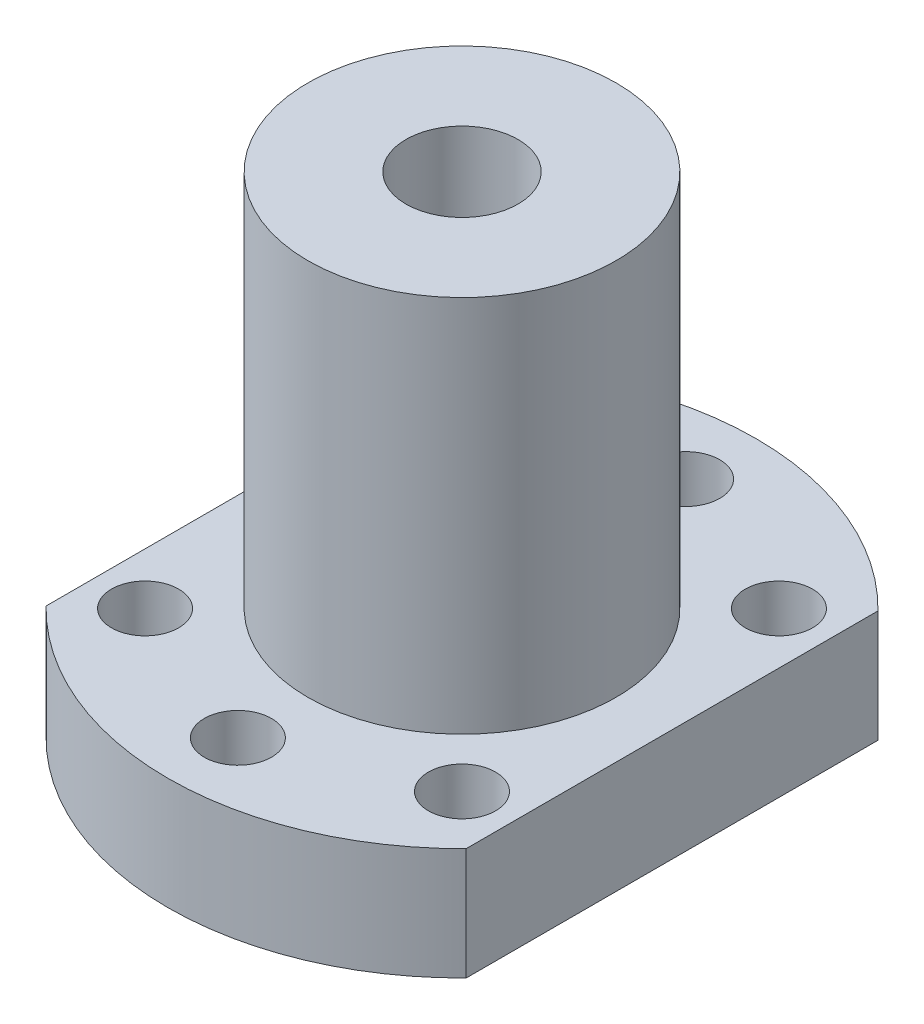
SolidWorks part; units mm, degrees
material "1060 合金"
ref_plane "前视基准面" through (0, 0, 0) normal (0, 0, 1) x (1, 0, 0)
ref_plane "上视基准面" through (0, 0, 0) normal (0, 1, 0) x (1, 0, 0)
ref_plane "右视基准面" through (0, 0, 0) normal (1, 0, 0) x (0, 0, -1)
sketch "草图1" plane through (0, 0, 0) normal (0, 1, 0) x (1, 0, 0)
  line L0 (-15, 14.6969) -> (-15, -14.6969)
  line L1 (15, 14.6969) -> (15, -14.6969)
  arc A0 (-15, -14.6969) -> (15, -14.6969) centre (0, 0) ccw
  arc A1 (15, 14.6969) -> (-15, 14.6969) centre (0, 0) ccw
  dimension "D1" = 15
  dimension "D3" = 42
  dimension "D2" = 15
extrude "凸台-拉伸1" add sketch "草图1" along normal blind 8
sketch "草图2" plane through (0, 8, 0) normal (0, 1, 0) x (1, 0, 0)
  circle A0 centre (0, 0) radius 4
  dimension "D1" = 8
extrude "切除-拉伸1" cut sketch "草图2" against normal through all
sketch "草图3" plane through (0, 8, 0) normal (0, 1, 0) x (1, 0, 0)
  circle A1 centre (-11.3137, 11.3137) radius 2.4
  dimension "D1" = 4.8
  dimension "D2" = 16
extrude "切除-拉伸2" cut sketch "草图3" against normal blind 8
pattern_circular "阵列(圆周)2" count 8 over 360 about axis through (0, 8, 0) along (0, 1, 0) skipping 1, 5 of "切除-拉伸2"
sketch "草图4" plane through (0, 8, 0) normal (0, 1, 0) x (1, 0, 0)
  circle A0 centre (0, 0) radius 11
extrude "凸台-拉伸2" add sketch "草图4" along normal blind 27
sketch "草图5" plane through (0, 35, 0) normal (0, 1, 0) x (1, 0, 0)
  circle A0 centre (0, 0) radius 4
  dimension "D1" = 8
extrude "切除-拉伸3" cut sketch "草图5" against normal through all
